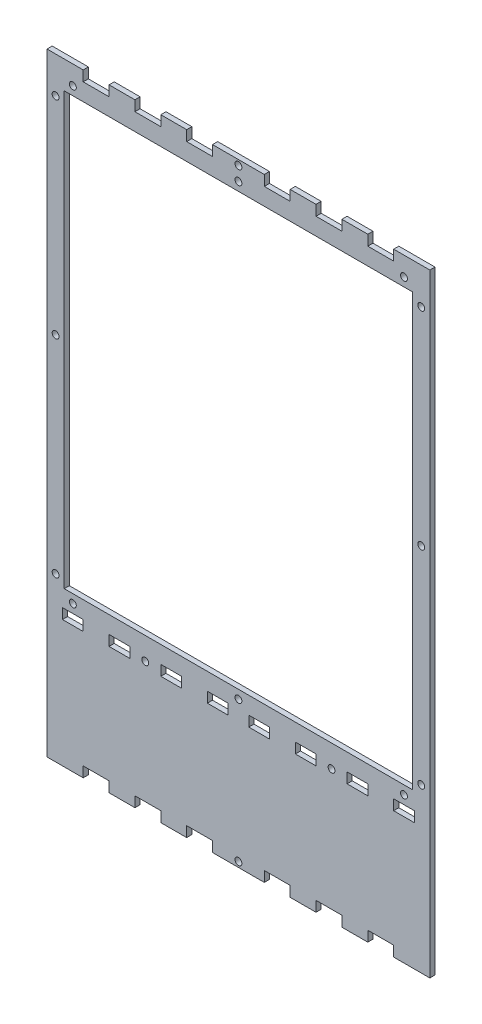
SolidWorks part; units mm, degrees
ref_plane "Plan de face" through (0, 0, 0) normal (0, 0, 1) x (1, 0, 0)
ref_plane "Plan de dessus" through (0, 0, 0) normal (0, 1, 0) x (1, 0, 0)
ref_plane "Plan de droite" through (0, 0, 0) normal (1, 0, 0) x (0, 0, -1)
sketch "Esquisse1" plane through (0, 0, 0) normal (0, 0, 1) x (1, 0, 0)
  line L1 (-49.5276, 73.9077) -> (172.4724, 73.9077)
  line L2 (-49.5276, 73.9077) -> (-49.5276, -281.5923)
  line L3 (-49.5276, -281.5923) -> (172.4724, -281.5923)
  line L4 (172.4724, 73.9077) -> (172.4724, -281.5923)
  dimension "D1" = 222
  dimension "D2" = 355.5
extrude "Boss.-Extru.1" add sketch "Esquisse1" along normal blind 3
sketch "Esquisse2" plane through (0, 0, 3) normal (0, 0, 1) x (1, 0, 0)
  line L0 (61.4724, 73.9077) -> (61.4724, 67.9077) construction
  line L1 (172.4724, 73.9077) -> (-49.5276, 73.9077) construction
  line L2 (-49.5276, 67.9077) -> (172.4724, 67.9077) construction
  line L3 (-49.5276, 73.9077) -> (-49.5276, -281.5923) construction
  line L4 (172.4724, -281.5923) -> (172.4724, 73.9077) construction
  line L5 (16.4724, 73.9077) -> (16.4724, 67.9077)
  line L6 (76.4724, 73.9077) -> (91.4724, 73.9077)
  line L7 (76.4724, 73.9077) -> (76.4724, 67.9077)
  line L8 (76.4724, 67.9077) -> (91.4724, 67.9077)
  line L9 (91.4724, 73.9077) -> (91.4724, 67.9077)
  line L10 (151.4724, 73.9077) -> (136.4724, 73.9077)
  line L11 (151.4724, 73.9077) -> (151.4724, 67.9077)
  line L12 (151.4724, 67.9077) -> (136.4724, 67.9077)
  line L13 (136.4724, 73.9077) -> (136.4724, 67.9077)
  line L14 (121.4724, 73.9077) -> (106.4724, 73.9077)
  line L15 (121.4724, 73.9077) -> (121.4724, 67.9077)
  line L16 (121.4724, 67.9077) -> (106.4724, 67.9077)
  line L17 (106.4724, 73.9077) -> (106.4724, 67.9077)
  line L18 (1.4724, 67.9077) -> (16.4724, 67.9077)
  line L19 (1.4724, 73.9077) -> (1.4724, 67.9077)
  line L20 (1.4724, 73.9077) -> (16.4724, 73.9077)
  line L21 (-13.5276, 73.9077) -> (-13.5276, 67.9077)
  line L22 (-28.5276, 67.9077) -> (-13.5276, 67.9077)
  line L23 (-28.5276, 73.9077) -> (-28.5276, 67.9077)
  line L24 (-28.5276, 73.9077) -> (-13.5276, 73.9077)
  line L25 (31.4724, 73.9077) -> (31.4724, 67.9077)
  line L26 (46.4724, 67.9077) -> (31.4724, 67.9077)
  line L27 (46.4724, 73.9077) -> (46.4724, 67.9077)
  line L28 (46.4724, 73.9077) -> (31.4724, 73.9077)
  line L29 (-49.5276, -103.8423) -> (172.4724, -103.8423) construction
  line L30 (-49.5276, -275.5923) -> (172.4724, -275.5923) construction
  line L31 (61.4724, -281.5923) -> (61.4724, -275.5923) construction
  line L32 (46.4724, -281.5923) -> (31.4724, -281.5923)
  line L33 (46.4724, -281.5923) -> (46.4724, -275.5923)
  line L34 (46.4724, -275.5923) -> (31.4724, -275.5923)
  line L35 (31.4724, -281.5923) -> (31.4724, -275.5923)
  line L36 (-28.5276, -281.5923) -> (-13.5276, -281.5923)
  line L37 (-28.5276, -281.5923) -> (-28.5276, -275.5923)
  line L38 (-28.5276, -275.5923) -> (-13.5276, -275.5923)
  line L39 (-13.5276, -281.5923) -> (-13.5276, -275.5923)
  line L40 (1.4724, -281.5923) -> (16.4724, -281.5923)
  line L41 (1.4724, -281.5923) -> (1.4724, -275.5923)
  line L42 (1.4724, -275.5923) -> (16.4724, -275.5923)
  line L43 (106.4724, -281.5923) -> (106.4724, -275.5923)
  line L44 (121.4724, -275.5923) -> (106.4724, -275.5923)
  line L45 (121.4724, -281.5923) -> (121.4724, -275.5923)
  line L46 (121.4724, -281.5923) -> (106.4724, -281.5923)
  line L47 (136.4724, -281.5923) -> (136.4724, -275.5923)
  line L48 (151.4724, -275.5923) -> (136.4724, -275.5923)
  line L49 (151.4724, -281.5923) -> (151.4724, -275.5923)
  line L50 (151.4724, -281.5923) -> (136.4724, -281.5923)
  line L51 (91.4724, -281.5923) -> (91.4724, -275.5923)
  line L52 (76.4724, -275.5923) -> (91.4724, -275.5923)
  line L53 (76.4724, -281.5923) -> (76.4724, -275.5923)
  line L54 (76.4724, -281.5923) -> (91.4724, -281.5923)
  line L55 (16.4724, -281.5923) -> (16.4724, -275.5923)
  circle A0 centre (61.4724, 70.9077) radius 2
  circle A1 centre (61.4724, -278.5923) radius 2
  dimension "D8" = 4
  dimension "D1" = 6
  dimension "D2" = 15
  dimension "D3" = 15
  dimension "D4" = 15
  dimension "D5" = 15
  dimension "D6" = 15
  dimension "D7" = 15
extrude "Enlèv. mat.-Extru.1" cut sketch "Esquisse2" against normal blind 3
sketch "Esquisse3" plane through (0, 0, 3) normal (0, 0, 1) x (1, 0, 0)
  line L0 (-49.5276, -208.0923) -> (172.4724, -208.0923) construction
  line L1 (-49.5276, 73.9077) -> (-49.5276, -281.5923) construction
  line L2 (172.4724, -281.5923) -> (172.4724, 73.9077) construction
  line L3 (-49.5276, -281.5923) -> (-28.5276, -281.5923) construction
  line L4 (-49.5276, -202.0923) -> (172.4724, -202.0923) construction
  line L5 (61.4724, -202.0923) -> (61.4724, -208.0923) construction
  line L6 (-1.5276, -205.0923) -> (16.4724, -205.0923) construction
  line L7 (55.4724, -202.0923) -> (43.4724, -202.0923)
  line L8 (55.4724, -202.0923) -> (55.4724, -208.0923)
  line L9 (55.4724, -208.0923) -> (43.4724, -208.0923)
  line L10 (43.4724, -202.0923) -> (43.4724, -208.0923)
  line L11 (28.4724, -202.0923) -> (16.4724, -202.0923)
  line L12 (28.4724, -202.0923) -> (28.4724, -208.0923)
  line L13 (28.4724, -208.0923) -> (16.4724, -208.0923)
  line L14 (16.4724, -202.0923) -> (16.4724, -208.0923)
  line L15 (-1.5276, -202.0923) -> (-13.5276, -202.0923)
  line L16 (-1.5276, -202.0923) -> (-1.5276, -208.0923)
  line L17 (-1.5276, -208.0923) -> (-13.5276, -208.0923)
  line L18 (-13.5276, -202.0923) -> (-13.5276, -208.0923)
  line L19 (-28.5276, -202.0923) -> (-40.5276, -202.0923)
  line L20 (-28.5276, -202.0923) -> (-28.5276, -208.0923)
  line L21 (-28.5276, -208.0923) -> (-40.5276, -208.0923)
  line L22 (-40.5276, -202.0923) -> (-40.5276, -208.0923)
  line L23 (124.4724, -205.0923) -> (106.4724, -205.0923) construction
  line L24 (163.4724, -202.0923) -> (163.4724, -208.0923)
  line L25 (151.4724, -208.0923) -> (163.4724, -208.0923)
  line L26 (151.4724, -202.0923) -> (151.4724, -208.0923)
  line L27 (151.4724, -202.0923) -> (163.4724, -202.0923)
  line L28 (136.4724, -202.0923) -> (136.4724, -208.0923)
  line L29 (124.4724, -208.0923) -> (136.4724, -208.0923)
  line L30 (124.4724, -202.0923) -> (124.4724, -208.0923)
  line L31 (124.4724, -202.0923) -> (136.4724, -202.0923)
  line L32 (106.4724, -202.0923) -> (106.4724, -208.0923)
  line L33 (94.4724, -208.0923) -> (106.4724, -208.0923)
  line L34 (94.4724, -202.0923) -> (94.4724, -208.0923)
  line L35 (94.4724, -202.0923) -> (106.4724, -202.0923)
  line L36 (79.4724, -202.0923) -> (79.4724, -208.0923)
  line L37 (67.4724, -208.0923) -> (79.4724, -208.0923)
  line L38 (67.4724, -202.0923) -> (67.4724, -208.0923)
  line L39 (67.4724, -202.0923) -> (79.4724, -202.0923)
  circle A0 centre (7.4724, -205.0923) radius 2
  circle A1 centre (115.4724, -205.0923) radius 2
  dimension "D11" = 4
  dimension "D1" = 73.5
  dimension "D2" = 6
  dimension "D3" = 12
  dimension "D4" = 12
  dimension "D5" = 12
  dimension "D6" = 12
  dimension "D7" = 6
  dimension "D8" = 15
  dimension "D9" = 18
  dimension "D10" = 15
extrude "Enlèv. mat.-Extru.2" cut sketch "Esquisse3" against normal blind 3
sketch "Esquisse4" plane through (0, 0, 3) normal (0, 0, 1) x (1, 0, 0)
  line L0 (-49.5276, 73.9077) -> (-49.5276, -281.5923) construction
  line L1 (-39.5276, 57.9077) -> (162.4724, 57.9077)
  line L2 (-39.5276, 57.9077) -> (-39.5276, -192.0923)
  line L3 (-39.5276, -192.0923) -> (162.4724, -192.0923)
  line L4 (162.4724, 57.9077) -> (162.4724, -192.0923)
  line L5 (172.4724, -281.5923) -> (172.4724, 73.9077) construction
  line L6 (106.4724, -202.0923) -> (94.4724, -202.0923) construction
  line L7 (76.4724, 67.9077) -> (91.4724, 67.9077) construction
  line L8 (-49.5276, -187.0923) -> (-39.5276, -187.0923) construction
  line L9 (-34.5276, -192.0923) -> (-34.5276, -202.0923) construction
  line L10 (-28.5276, -202.0923) -> (-40.5276, -202.0923) construction
  line L11 (61.4724, 57.9077) -> (61.4724, -192.0923) construction
  line L12 (157.4724, -192.0923) -> (157.4724, -202.0923) construction
  line L13 (172.4724, -187.0923) -> (162.4724, -187.0923) construction
  line L14 (-39.5276, -67.0923) -> (162.4724, -67.0923) construction
  line L15 (172.4724, 52.9077) -> (162.4724, 52.9077) construction
  line L16 (157.4724, 57.9077) -> (157.4724, 67.9077) construction
  line L17 (-34.5276, 57.9077) -> (-34.5276, 67.9077) construction
  line L18 (-49.5276, 52.9077) -> (-39.5276, 52.9077) construction
  line L19 (-39.5276, -67.0923) -> (-49.5276, -67.0923) construction
  line L20 (162.4724, -67.0923) -> (172.4724, -67.0923) construction
  line L21 (46.4724, 67.9077) -> (76.4724, 67.9077) construction
  line L22 (61.4724, 57.9077) -> (61.4724, 67.9077) construction
  line L23 (55.4724, -202.0923) -> (67.4724, -202.0923) construction
  line L24 (61.4724, -192.0923) -> (61.4724, -202.0923) construction
  circle A0 centre (-44.5276, -187.0923) radius 2
  circle A1 centre (-34.5276, -197.0923) radius 2
  circle A2 centre (157.4724, -197.0923) radius 2
  circle A3 centre (167.4724, -187.0923) radius 2
  circle A4 centre (167.4724, 52.9077) radius 2
  circle A5 centre (157.4724, 62.9077) radius 2
  circle A6 centre (-34.5276, 62.9077) radius 2
  circle A7 centre (-44.5276, 52.9077) radius 2
  circle A8 centre (-44.5276, -67.0923) radius 2
  circle A9 centre (167.4724, -67.0923) radius 2
  circle A10 centre (61.4724, 62.9077) radius 2
  circle A11 centre (61.4724, -197.0923) radius 2
  dimension "D5" = 4
  dimension "D6" = 4
  dimension "D9" = 4
  dimension "D10" = 4
  dimension "D11" = 4
  dimension "D12" = 4
  dimension "D1" = 10
  dimension "D2" = 10
  dimension "D3" = 10
  dimension "D4" = 10
  dimension "D7" = 5
  dimension "D8" = 5
extrude "Enlèv. mat.-Extru.3" cut sketch "Esquisse4" against normal blind 3
